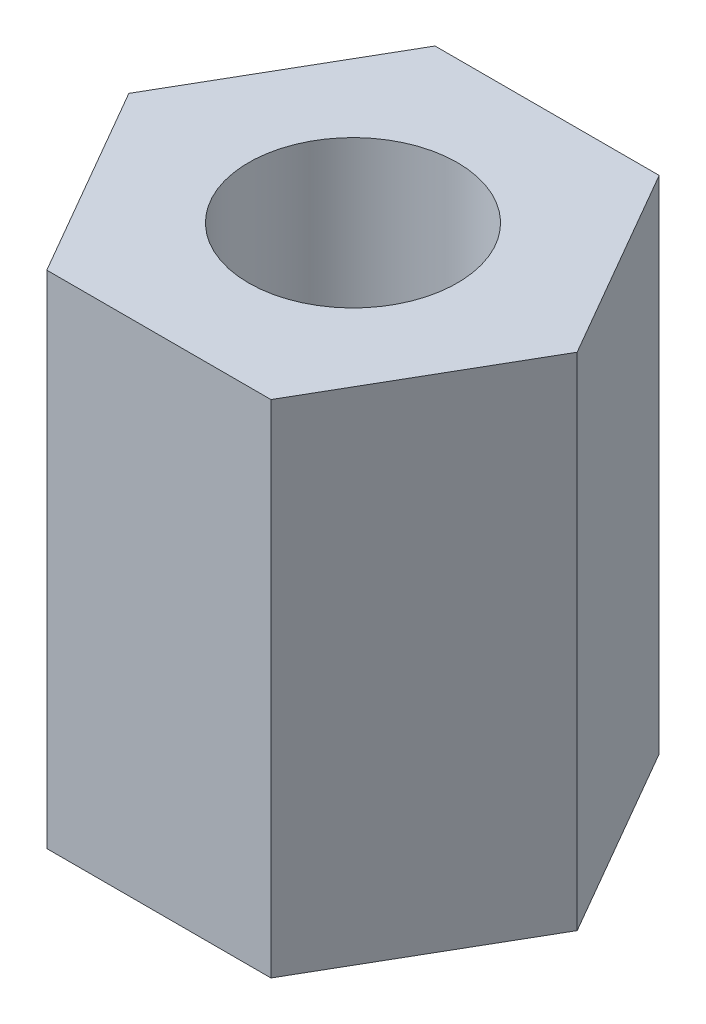
SolidWorks part; units mm, degrees
ref_plane "Front" through (0, 0, 0) normal (0, 0, 1) x (1, 0, 0)
ref_plane "Top" through (0, 0, 0) normal (0, 1, 0) x (1, 0, 0)
ref_plane "Right" through (0, 0, 0) normal (1, 0, 0) x (0, 0, -1)
sketch "Sketch1" plane through (0, 0, 0) normal (0, 1, 0) x (1, 0, 0)
  line L1 (2.6847, 0) -> (1.3423, 2.325)
  line L2 (1.3423, 2.325) -> (-1.3423, 2.325)
  line L3 (-1.3423, 2.325) -> (-2.6847, 0)
  line L4 (-2.6847, 0) -> (-1.3423, -2.325)
  line L5 (-1.3423, -2.325) -> (1.3423, -2.325)
  line L6 (1.3423, -2.325) -> (2.6847, 0)
  circle A0 centre (0, 0) radius 2.325 construction
  dimension "D1" = 4.65
extrude "base" add sketch "Sketch1" along normal blind 6
sketch "Sketch2" plane through (0, 6, 0) normal (0, 1, 0) x (1, 0, 0)
  circle A0 centre (0, 0) radius 1.25
  dimension "D1" = 2.5
extrude "hole" cut sketch "Sketch2" against normal blind 6
